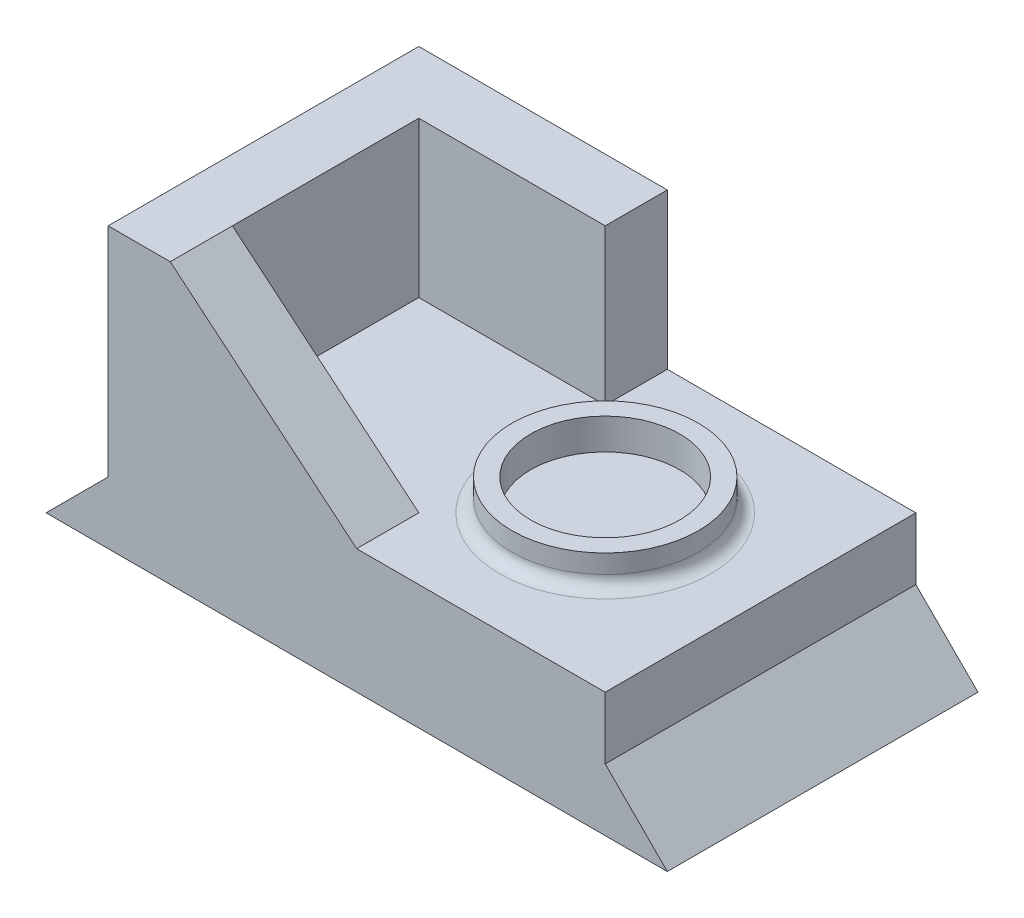
SolidWorks part; units mm, degrees
material "1060 Alloy"
ref_plane "Front Plane" through (0, 0, 0) normal (0, 0, 1) x (1, 0, 0)
ref_plane "Top Plane" through (0, 0, 0) normal (0, 1, 0) x (1, 0, 0)
ref_plane "Right Plane" through (0, 0, 0) normal (1, 0, 0) x (0, 0, -1)
sketch "Esquisse1" plane through (0, 0, 0) normal (0, 0, 1) x (1, 0, 0)
  line L0 (0, 0) -> (10, 10)
  line L1 (10, 10) -> (10, 45)
  line L2 (10, 45) -> (20, 45)
  line L3 (20, 45) -> (50, 20)
  line L4 (50, 20) -> (90, 20)
  line L5 (90, 20) -> (90, 10)
  line L6 (90, 10) -> (100, 0)
  line L7 (100, 0) -> (0, 0)
  dimension "D1" = 10
  dimension "D2" = 45
  dimension "D3" = 10
  dimension "D4" = 30
  dimension "D5" = 80
  dimension "D6" = 100
  dimension "D7" = 25
  dimension "D8" = 10
  dimension "D9" = 10
  dimension "D10" = 10
  dimension "D11" = 10
extrude "Boss.-Extru.1" add sketch "Esquisse1" against normal blind 50
sketch "Esquisse2" plane through (0, 0, -50) normal (0, 0, -1) x (-1, 0, 0)
  line L1 (-20, 45) -> (-20, 20)
  line L2 (-20, 20) -> (-50, 20)
  line L3 (-50, 20) -> (-20, 45)
  dimension "D1" = 25
  dimension "D2" = 30
extrude "Enlèv. mat.-Extru.1" cut sketch "Esquisse2" against normal blind 40
sketch "Esquisse4" plane through (0, 0, -50) normal (0, 0, -1) x (-1, 0, 0)
  line L1 (-50, 20) -> (-20, 20)
  line L2 (-50, 20) -> (-50, 45)
  line L3 (-50, 45) -> (-20, 45)
  line L4 (-20, 20) -> (-20, 45)
  dimension "D1" = 30
  dimension "D2" = 25
extrude "Boss.-Extru.3" add sketch "Esquisse4" against normal blind 10
sketch "Esquisse5" plane through (0, 20, 0) normal (0, 1, 0) x (1, 0, 0)
  line L0 (65, 59.3535) -> (65, -9.3535) construction
  line L1 (90, 50) -> (90, 0) construction
  line L2 (50, 40) -> (50, 50) construction
  line L3 (90, 0) -> (50, 0) construction
  circle A0 centre (65, 25) radius 15
  circle A1 centre (65, 25) radius 12
  point P6 (65, 25)
  dimension "D4" = 30
  dimension "D5" = 24
  dimension "D1" = 25
  dimension "D2" = 15
  dimension "D3" = 25
  dimension "D7" = 15
extrude "Boss.-Extru.4" add sketch "Esquisse5" along normal blind 5
fillet "Congé2" radius 2 1 edges at (65, 20, -10)
